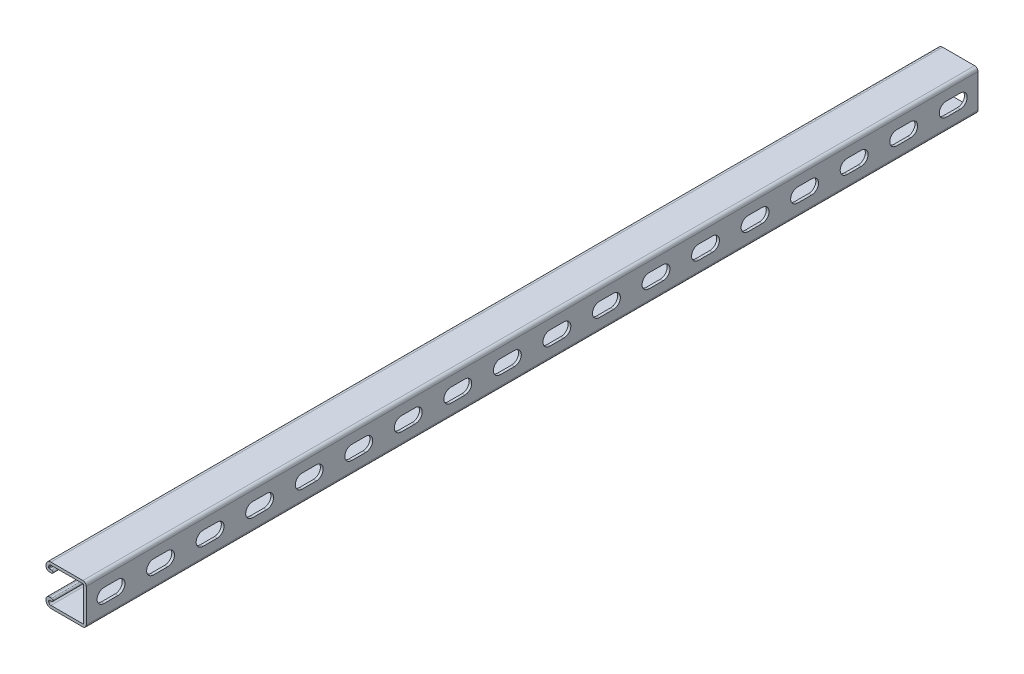
SolidWorks part; units mm, degrees
ref_plane "Front Plane" through (0, 0, 0) normal (0, 0, 1) x (1, 0, 0)
ref_plane "Top Plane" through (0, 0, 0) normal (0, 1, 0) x (1, 0, 0)
ref_plane "Right Plane" through (0, 0, 0) normal (1, 0, 0) x (0, 0, -1)
sketch "Sketch1" plane through (0, 0, 0) normal (0, 0, 1) x (1, 0, 0)
  line L0 (0, 0) -> (-41.275, 0) construction
  line L3 (-41.275, 20.6375) -> (0, 20.6375) construction
  line L4 (-41.275, 20.6375) -> (-41.275, -20.6375) construction
  line L5 (-41.275, -20.6375) -> (0, -20.6375) construction
  line L6 (0, 20.6375) -> (0, -20.6375) construction
  line L7 (-36.2267, 20.6375) -> (-3.4607, 20.6375)
  line L8 (0, 17.1767) -> (0, -17.1767)
  line L9 (-2.794, -17.1767) -> (-2.794, 17.1767)
  line L10 (-3.4608, 17.8435) -> (-36.2267, 17.8435)
  line L11 (-41.275, 15.5892) -> (-41.275, 14.5732)
  line L12 (-37.8142, 11.1125) -> (-35.5346, 11.1125)
  line L14 (-35.5346, 13.9065) -> (-37.8142, 13.9065)
  line L15 (-38.481, 14.5732) -> (-38.481, 15.5892)
  line L16 (-38.481, -14.5733) -> (-38.481, -15.5893)
  line L17 (-35.5346, -13.9065) -> (-37.8142, -13.9065)
  line L18 (-37.8142, -11.1125) -> (-35.5346, -11.1125)
  line L19 (-41.275, -15.5893) -> (-41.275, -14.5733)
  line L20 (-3.4607, -17.8435) -> (-36.2267, -17.8435)
  line L21 (-36.2267, -20.6375) -> (-3.4607, -20.6375)
  line L22 (-2.794, -20.6375) -> (-2.794, 20.6375) construction
  arc A1 (0, 17.1767) -> (-3.4607, 20.6375) centre (-3.4607, 17.1767) ccw
  arc A2 (-2.794, 17.1767) -> (-3.4608, 17.8435) centre (-3.4607, 17.1767) ccw
  arc A4 (-36.2267, 20.6375) -> (-41.275, 15.5892) centre (-36.2267, 15.5892) ccw
  arc A5 (-41.275, 14.5732) -> (-37.8142, 11.1125) centre (-37.8142, 14.5732) ccw
  arc A6 (-35.5346, 11.1125) -> (-35.5346, 13.9065) centre (-35.5346, 12.5095) ccw
  arc A7 (-37.8142, 13.9065) -> (-38.481, 14.5732) centre (-37.8142, 14.5732) cw
  arc A8 (-38.481, 15.5892) -> (-36.2267, 17.8435) centre (-36.2267, 15.5892) cw
  arc A9 (-38.481, -15.5893) -> (-36.2267, -17.8435) centre (-36.2267, -15.5893) ccw
  arc A10 (-37.8142, -13.9065) -> (-38.481, -14.5733) centre (-37.8142, -14.5733) ccw
  arc A11 (-35.5346, -11.1125) -> (-35.5346, -13.9065) centre (-35.5346, -12.5095) cw
  arc A12 (-41.275, -14.5733) -> (-37.8142, -11.1125) centre (-37.8142, -14.5733) cw
  arc A13 (-36.2267, -20.6375) -> (-41.275, -15.5893) centre (-36.2267, -15.5893) cw
  arc A14 (-2.794, -17.1767) -> (-3.4607, -17.8435) centre (-3.4607, -17.1767) cw
  arc A15 (0, -17.1767) -> (-3.4607, -20.6375) centre (-3.4607, -17.1767) cw
  point P24 (0, 20.6375)
  point P65 (-2.794, 0)
  dimension "D1" = 3.4608
  dimension "D2" = 5.0482
  dimension "D3" = 3.4608
  dimension "Ht." = 41.275
  dimension "Wd." = 41.275
  dimension "Thk." = 2.794
  dimension "D4" = 9.525
  dimension "D5" = 7.1374
extrude "Boss-Extrude1" add sketch "Sketch1" against normal blind 914.4
sketch "Sketch3" plane through (0, 0, 0) normal (1, 0, 0) x (0, 0, -1)
  line L0 (0, 0) -> (914.4, 0) construction
  point P2 (101.6, 0)
  point P3 (812.8, 0)
  dimension "D1" = 101.6
  dimension "D2" = 101.6
  dimension "D3" = 914.4
sketch "Sketch2" plane through (0, 0, 0) normal (1, 0, 0) x (0, 0, -1)
  line L0 (18.2562, 0) -> (32.5437, 0) construction
  line L1 (18.2562, 7.1437) -> (32.5437, 7.1437)
  line L2 (18.2562, -7.1437) -> (32.5437, -7.1437)
  line L3 (18.2562, 0) -> (0, 0) construction
  line L4 (25.4, 0) -> (76.2, 0) construction
  line L5 (0, -17.1767) -> (0, 17.1767) construction
  arc A0 (18.2562, 7.1437) -> (18.2562, -7.1437) centre (18.2562, 0) ccw
  arc A1 (32.5437, -7.1437) -> (32.5437, 7.1437) centre (32.5437, 0) ccw
  point P3 (25.4, 0)
  dimension "Slot Lg." = 28.575
  dimension "D2" = 25.4
  dimension "Slot Wd." = 14.2875
  dimension "Slot Ctr." = 50.8
  dimension "Hole to End" = 11.1125
extrude "Cut-Extrude1" cut sketch "Sketch2" against normal up to vertex (2.794 mm away) up to point (-2.794, 0, 0)
pattern_linear "LPattern1" count 18 spacing 50.8 along (0, 0, -1) of "Cut-Extrude1"
equation "\"D1@LPattern1\" = \"Slot Ctr.@Sketch2\""
equation "\"Hole Count@LPattern1\" = \"Lg.@Boss-Extrude1\" / \"D1@LPattern1\""
equation "\"D3@Sketch3\" = \"Lg.@Boss-Extrude1\""
